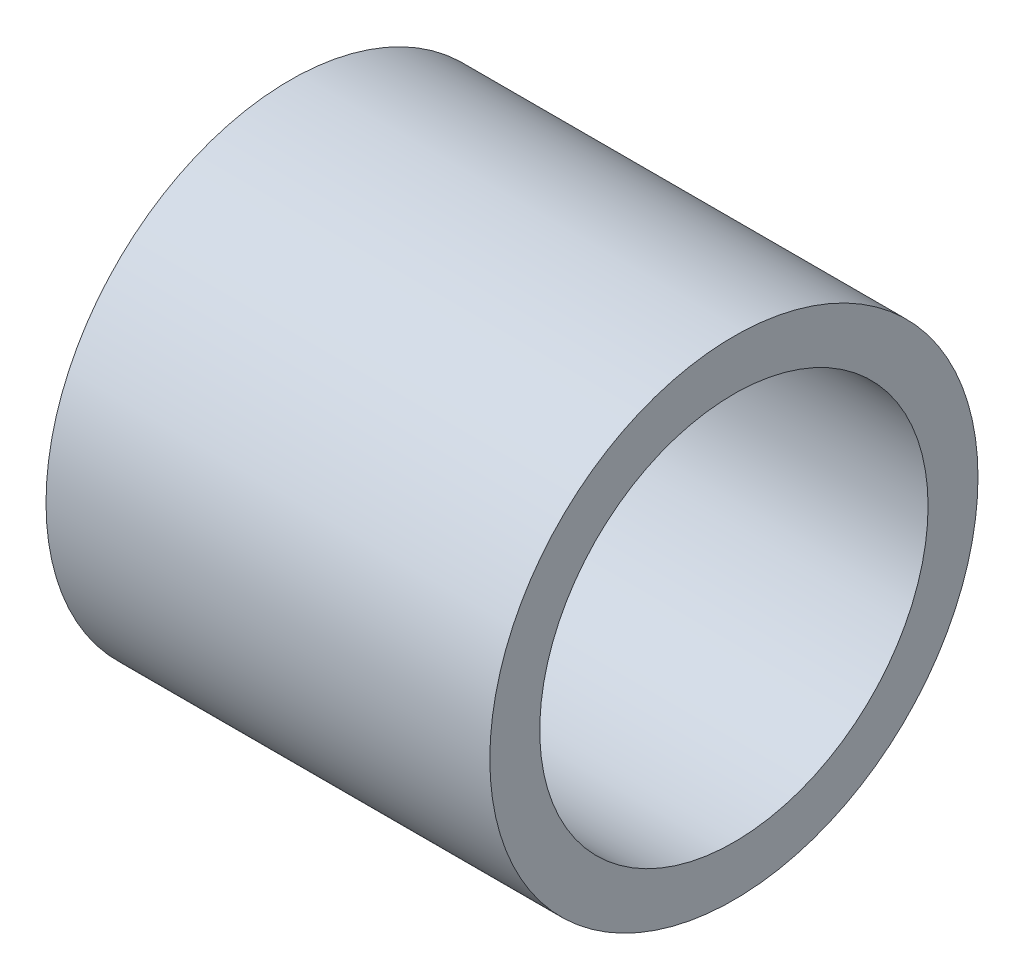
SolidWorks part; units mm, degrees
material "Plain Carbon Steel"
ref_plane "Front Plane" through (0, 0, 0) normal (0, 0, 1) x (1, 0, 0)
ref_plane "Top Plane" through (0, 0, 0) normal (0, 1, 0) x (1, 0, 0)
ref_plane "Right Plane" through (0, 0, 0) normal (1, 0, 0) x (0, 0, -1)
sketch "Sketch1" plane through (0, 0, 0) normal (1, 0, 0) x (0, 0, -1)
  circle A1 centre (0, 0) radius 11
  circle A2 centre (0, 0) radius 8.75
  dimension "ID" = 17.5
  dimension "OD" = 22
extrude "Extrude1" add sketch "Sketch1" along normal blind 20
